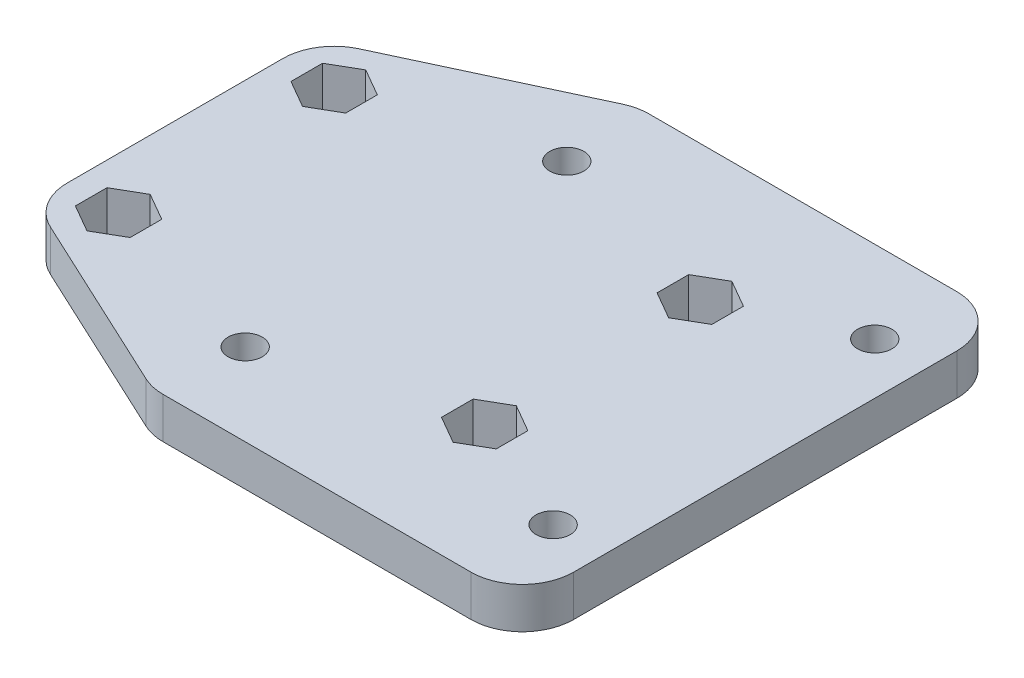
SolidWorks part; units mm, degrees
ref_plane "Front Plane" through (0, 0, 0) normal (0, 0, 1) x (1, 0, 0)
ref_plane "Top Plane" through (0, 0, 0) normal (0, 1, 0) x (1, 0, 0)
ref_plane "Right Plane" through (0, 0, 0) normal (1, 0, 0) x (0, 0, -1)
sketch "Sketch1" plane through (0, 0, 0) normal (0, 1, 0) x (1, 0, 0)
  line L0 (-28.5, -23.5) -> (-23.5, -23.5) construction
  line L7 (16.5, -23.5) -> (21.5, -23.5) construction
  line L10 (16.5, 23.5) -> (21.5, 23.5) construction
  line L13 (-28.5, 23.5) -> (-23.5, 23.5) construction
  line L16 (-59.75, 15.75) -> (-59.75, -15.75)
  line L17 (-55.4216, -22.5464) -> (-29.1716, -34.7964)
  line L18 (-26, -35.5) -> (19, -35.5)
  line L19 (26.5, -28) -> (26.5, 28)
  line L20 (19, 35.5) -> (-26, 35.5)
  line L21 (-29.1716, 34.7964) -> (-55.4216, 22.5464)
  circle A0 centre (-52.25, 15.75) radius 2.75
  circle A1 centre (-52.25, -15.75) radius 2.75
  circle A2 centre (1.25, -15.75) radius 2.75
  circle A3 centre (1.25, 15.75) radius 2.75
  circle A4 centre (-26, -23.5) radius 2.5
  circle A5 centre (19, -23.5) radius 2.5
  circle A6 centre (19, 23.5) radius 2.5
  circle A7 centre (-26, 23.5) radius 2.5
  circle A12 centre (-52.25, 15.75) radius 7.5
  circle A13 centre (-52.25, -15.75) radius 7.5
  circle A14 centre (-26, -28) radius 7.5
  circle A15 centre (19, -28) radius 7.5
  circle A16 centre (19, 28) radius 7.5
  circle A17 centre (-26, 28) radius 7.5
  dimension "D1" = 15
extrude "Boss-Extrude1" add sketch "Sketch1" along normal blind 6 contours A12 A0 | A17 L21 A12 L16 A13 L17 A14 L18 A15 L19 A16 L20 A3 A2 | A13 A1 | A14 A4 | A15 A5 | A16 A6 | A17 A7
sketch "Sketch2" plane through (0, 6, 0) normal (0, 1, 0) x (1, 0, 0)
  line L1 (-52.25, 11.1312) -> (-48.25, 13.4406)
  line L2 (-48.25, 13.4406) -> (-48.25, 18.0594)
  line L3 (-48.25, 18.0594) -> (-52.25, 20.3688)
  line L4 (-52.25, 20.3688) -> (-56.25, 18.0594)
  line L5 (-56.25, 18.0594) -> (-56.25, 13.4406)
  line L6 (-56.25, 13.4406) -> (-52.25, 11.1312)
  line L7 (-52.25, -11.1312) -> (-56.25, -13.4406)
  line L8 (-56.25, -13.4406) -> (-56.25, -18.0594)
  line L9 (-56.25, -18.0594) -> (-52.25, -20.3688)
  line L10 (-52.25, -20.3688) -> (-48.25, -18.0594)
  line L11 (-48.25, -18.0594) -> (-48.25, -13.4406)
  line L12 (-48.25, -13.4406) -> (-52.25, -11.1312)
  line L13 (-2.75, -18.0594) -> (1.25, -20.3688)
  line L14 (1.25, -20.3688) -> (5.25, -18.0594)
  line L15 (5.25, -18.0594) -> (5.25, -13.4406)
  line L16 (5.25, -13.4406) -> (1.25, -11.1312)
  line L17 (1.25, -11.1312) -> (-2.75, -13.4406)
  line L18 (-2.75, -13.4406) -> (-2.75, -18.0594)
  line L19 (1.25, 11.1312) -> (5.25, 13.4406)
  line L20 (5.25, 13.4406) -> (5.25, 18.0594)
  line L21 (5.25, 18.0594) -> (1.25, 20.3688)
  line L22 (1.25, 20.3688) -> (-2.75, 18.0594)
  line L23 (-2.75, 18.0594) -> (-2.75, 13.4406)
  line L24 (-2.75, 13.4406) -> (1.25, 11.1312)
  circle A0 centre (-52.25, 15.75) radius 4 construction
  circle A1 centre (-52.25, -15.75) radius 4 construction
  circle A2 centre (1.25, -15.75) radius 4 construction
  circle A3 centre (1.25, 15.75) radius 4 construction
  point P28 (0, 0)
  point P37 (0, 0)
  point P38 (0, 0)
  point P39 (0, 0)
  point P40 (1.25, -15.75)
  point P42 (-52.25, -15.75)
  point P44 (1.25, 15.75)
  point P46 (-52.25, 15.75)
  dimension "D1" = 8
extrude "Cut-Extrude1" cut sketch "Sketch2" against normal through all and the other way through all
